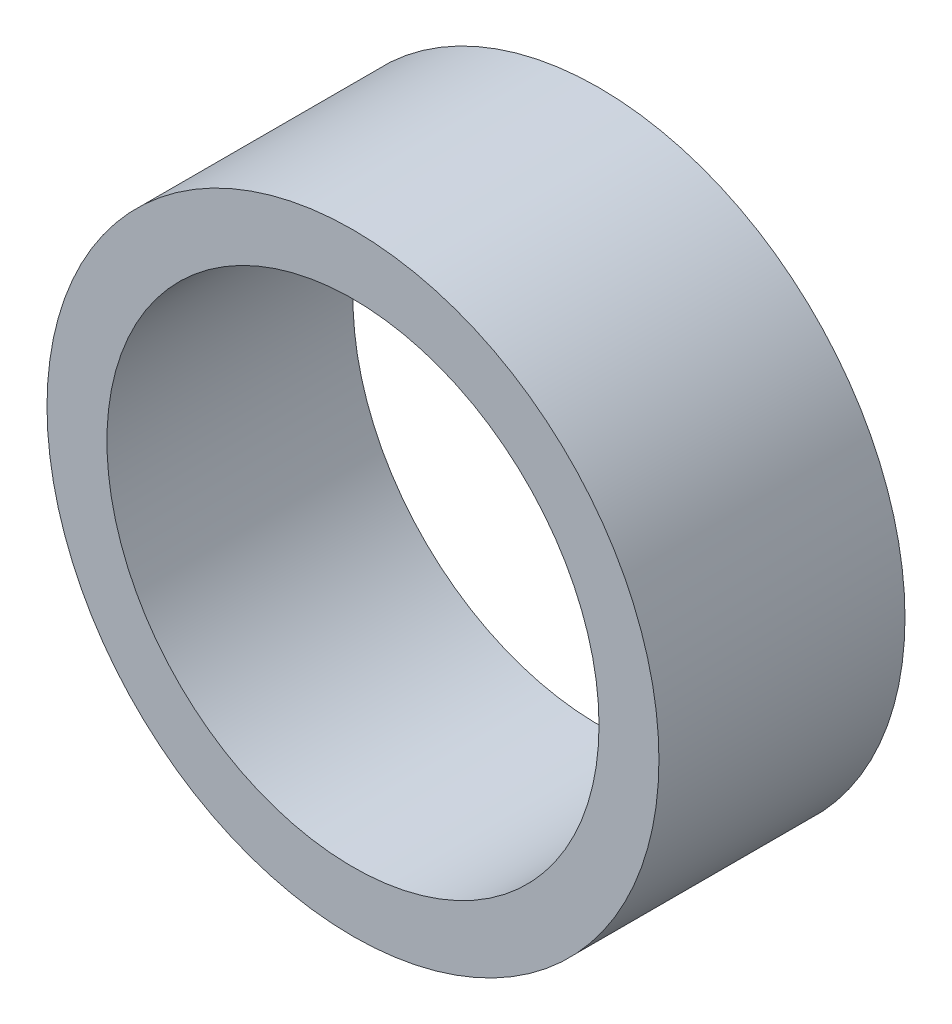
SolidWorks part; units mm, degrees
ref_plane "Front Plane" through (0, 0, 0) normal (0, 0, 1) x (1, 0, 0)
ref_plane "Top Plane" through (0, 0, 0) normal (0, 1, 0) x (1, 0, 0)
ref_plane "Right Plane" through (0, 0, 0) normal (1, 0, 0) x (0, 0, -1)
sketch "Sketch1" plane through (0, 0, 0) normal (0, 0, 1) x (1, 0, 0)
  circle A0 centre (0, 0) radius 24.87
  circle A1 centre (0, 0) radius 20
  dimension "D1" = 49.74
  dimension "D2" = 40
extrude "Boss-Extrude1" add sketch "Sketch1" along normal blind 20
